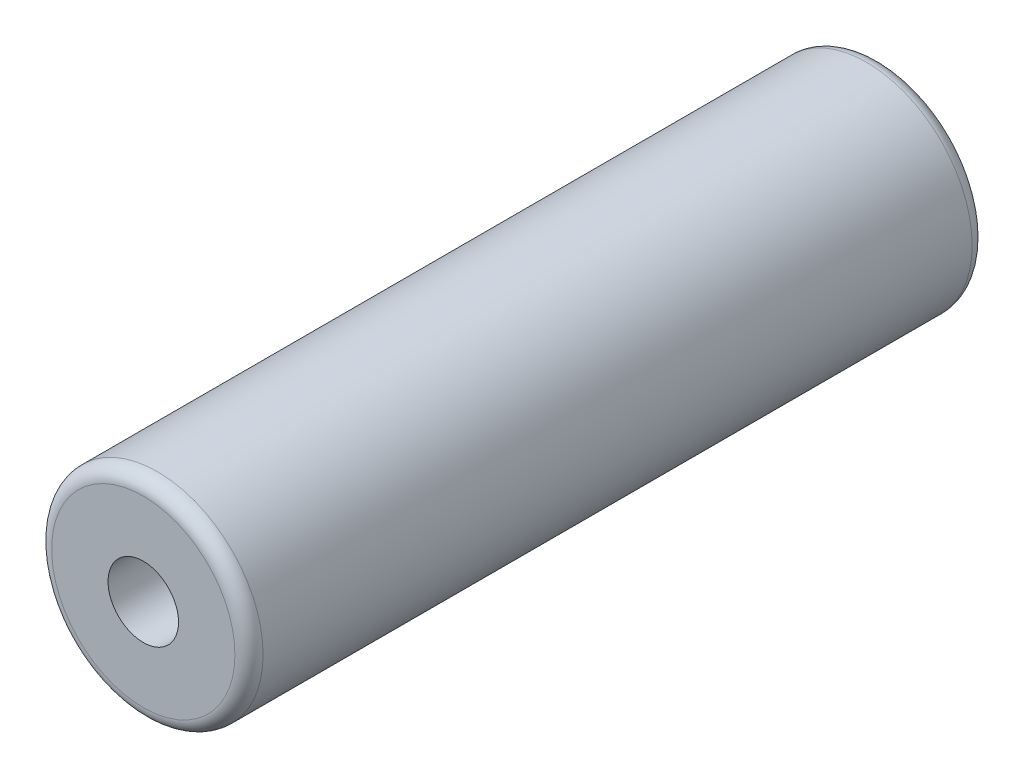
SolidWorks part; units mm, degrees
ref_plane "Alzado" through (0, 0, 0) normal (0, 0, 1) x (1, 0, 0)
ref_plane "Planta" through (0, 0, 0) normal (0, 1, 0) x (1, 0, 0)
ref_plane "Vista lateral" through (0, 0, 0) normal (1, 0, 0) x (0, 0, -1)
sketch "Croquis1" plane through (0, 0, 0) normal (0, 0, 1) x (1, 0, 0)
  circle A0 centre (0, 0) radius 7.5
  dimension "D1" = 15
extrude "Saliente-Extruir1" add sketch "Croquis1" along normal mid plane 52.3
hole_wizard "Taladro roscado M61" positions "Croquis3" profile "Croquis2" tap size "M6" standard "Is"
sketch "Croquis3" plane through (0, 0, 26.15) normal (0, 0, 1) x (1, 0, 0)
  point P0 (0, 0)
sketch "Croquis2" plane through (0, 0, 26.15) normal (1, 0, 0) x (0, -1, 0)
  line L0 (0, 0) -> (0, 18.5022)
  line L1 (0, 18.5022) -> (2.5, 17)
  line L2 (2.5, 17) -> (2.5, 0)
  line L5 (2.5, 0) -> (0, 0)
  line L10 (0, 18.5022) -> (-2.5, 17) construction
  line L11 (0, -6.35) -> (0, 107.95) construction
  dimension "Diámetro de perforador para roscar" = 5
  dimension "Profundidad de perforador para roscar" = 17
  dimension "Ángulo de perforador" = 118
cosmetic thread "Rosca de taladro1" parameters "D1"=12, "D2"=6
fillet "Redondeo1" radius 1 2 edges at (7.5, 0, -26.15) (7.5, 0, 26.15)
mirror "Simetría1" about plane through (0, 0, 0) normal (0, 0, 1) of "Taladro roscado M61"
